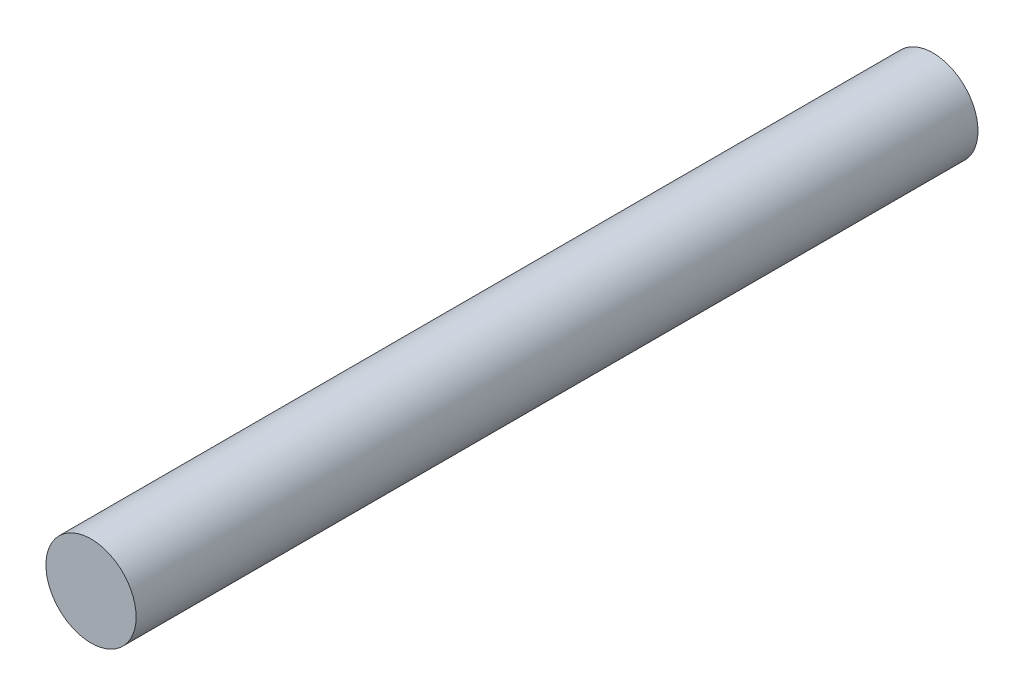
SolidWorks part; units mm, degrees
ref_plane "Front Plane" through (0, 0, 0) normal (0, 0, 1) x (1, 0, 0)
ref_plane "Top Plane" through (0, 0, 0) normal (0, 1, 0) x (1, 0, 0)
ref_plane "Right Plane" through (0, 0, 0) normal (1, 0, 0) x (0, 0, -1)
sketch "Sketch1" plane through (0, 0, 0) normal (0, 0, 1) x (1, 0, 0)
  circle A0 centre (0, 0) radius 3
  dimension "D1" = 6
extrude "Boss-Extrude1" add sketch "Sketch1" along normal blind 56
ref_point "Centre"
